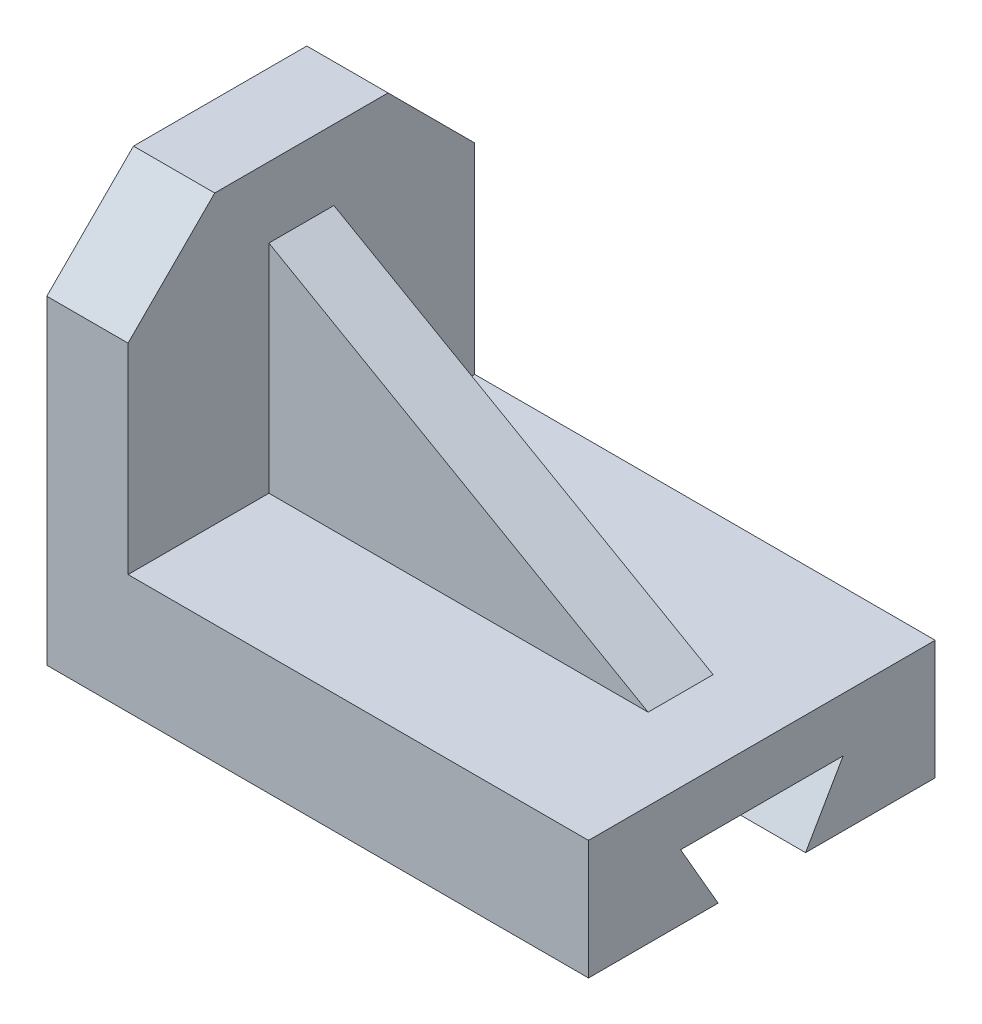
SolidWorks part; units mm, degrees
ref_plane "Front Plane" through (0, 0, 0) normal (0, 0, 1) x (1, 0, 0)
ref_plane "Top Plane" through (0, 0, 0) normal (0, 1, 0) x (1, 0, 0)
ref_plane "Right Plane" through (0, 0, 0) normal (1, 0, 0) x (0, 0, -1)
sketch "Sketch1" plane through (0, 0, 0) normal (0, 0, 1) x (1, 0, 0)
  line L1 (0, 0) -> (100, 0)
  line L2 (0, 0) -> (0, 22)
  line L3 (0, 22) -> (100, 22)
  line L4 (100, 0) -> (100, 22)
  dimension "D1" = 22
  dimension "D2" = 100
extrude "Boss-Extrude1" add sketch "Sketch1" along normal blind 64
sketch "Sketch2" plane through (0, 0, 0) normal (-1, 0, 0) x (0, 0, 1)
  line L0 (64, 0) -> (0, 0) construction
  line L1 (64, 0) -> (0, 0)
  line L2 (0, 0) -> (0, 59)
  line L3 (16, 75) -> (48, 75)
  line L4 (64, 59) -> (64, 0)
  line L5 (16, 75) -> (0, 59)
  line L6 (32, 0) -> (32, 78.2446) construction
  line L7 (48, 75) -> (64, 59)
  dimension "D1" = 75
  dimension "D2" = 32
  dimension "D3" = 22.6274
extrude "Boss-Extrude2" add sketch "Sketch2" against normal blind 15
sketch "Sketch3" plane through (15, 0, 0) normal (1, 0, 0) x (0, 0, -1)
  line L0 (-64, 22) -> (-64, 59) construction
  line L1 (-26, 22) -> (-38, 22)
  line L2 (-38, 22) -> (-38, 62)
  line L3 (-38, 62) -> (-26, 62)
  line L4 (-26, 22) -> (-26, 62)
  line L5 (0, 59) -> (0, 22) construction
  line L6 (-64, 22) -> (0, 22)
  line L7 (0, 22) -> (0, 59)
  line L8 (0, 59) -> (-16, 75)
  line L9 (-16, 75) -> (-48, 75)
  line L10 (-48, 75) -> (-64, 59)
  line L11 (-64, 59) -> (-64, 22)
  line L12 (-38, 22) -> (-26, 22)
  point P13 (-32, 62)
  line M12 (-64, 22) -> (0, 22)
  dimension "D2" = 26
  dimension "D3" = 40
  dimension "D4" = 26
  dimension "D1" = 0
extrude "Boss-Extrude3" add sketch "Sketch3" along normal blind 70 contours L4 L3 L2 M12
sketch "Sketch4" plane through (0, 0, 38) normal (0, 0, 1) x (1, 0, 0)
  line L0 (15, 62) -> (85, 22)
  line L1 (85, 22) -> (85, 62)
  line L2 (85, 62) -> (15, 62)
extrude "Cut-Extrude1" cut sketch "Sketch4" against normal blind 70
sketch "Sketch6" plane through (100, 0, 0) normal (1, 0, 0) x (0, 0, -1)
  line L0 (-64, 0) -> (0, 0) construction
  line L1 (-32, 0) -> (-32, 24) construction
  line L2 (-17, 12) -> (-47, 12)
  line L3 (-40.0718, 0) -> (-23.9282, 0)
  line L4 (-40.0718, 0) -> (-47, 12)
  line L5 (-23.9282, 0) -> (-17, 12)
  point P4 (-32, 12)
  point P12 (-32, 12)
  dimension "D1" = 12
  dimension "D2" = 15
  dimension "D3" = 60
extrude "Cut-Extrude2" cut sketch "Sketch6" against normal through all
